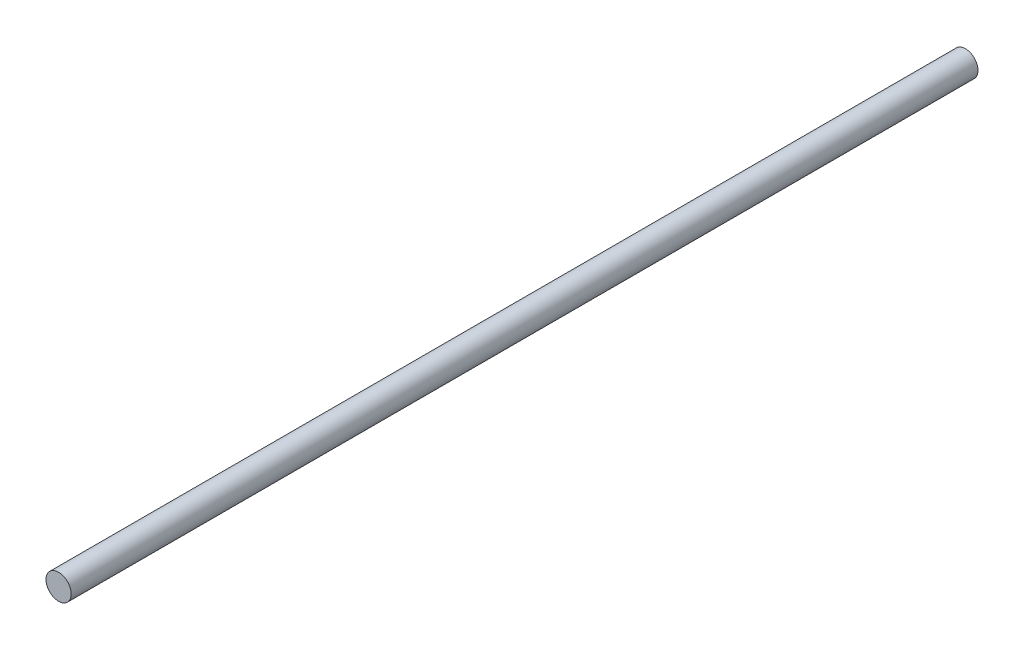
SolidWorks part; units mm, degrees
ref_plane "Plan de face" through (0, 0, 0) normal (0, 0, 1) x (1, 0, 0)
ref_plane "Plan de dessus" through (0, 0, 0) normal (0, 1, 0) x (1, 0, 0)
ref_plane "Plan de droite" through (0, 0, 0) normal (1, 0, 0) x (0, 0, -1)
sketch "Esquisse1" plane through (0, 0, 0) normal (0, 0, 1) x (1, 0, 0)
  circle A0 centre (0, 0) radius 4
  dimension "D1" = 8
extrude "Boss.-Extru.1" add sketch "Esquisse1" along normal blind 288
